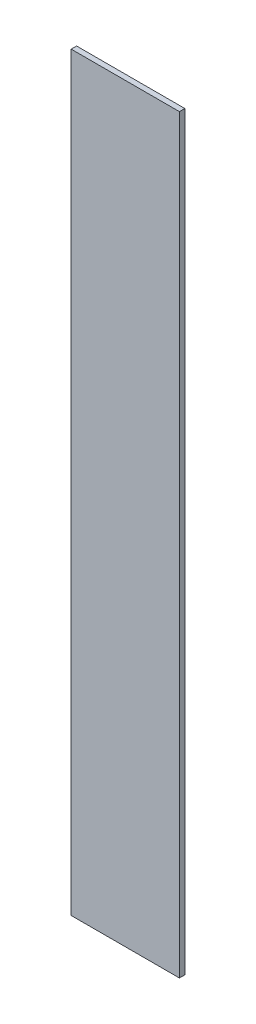
SolidWorks part; units mm, degrees
ref_plane "Plan de face" through (0, 0, 0) normal (0, 0, 1) x (1, 0, 0)
ref_plane "Plan de dessus" through (0, 0, 0) normal (0, 1, 0) x (1, 0, 0)
ref_plane "Plan de droite" through (0, 0, 0) normal (1, 0, 0) x (0, 0, -1)
sketch "Esquisse1" plane through (0, 0, 0) normal (0, 0, 1) x (1, 0, 0)
  line L1 (-60, -416) -> (60, -416)
  line L2 (-60, -416) -> (-60, 416)
  line L3 (-60, 416) -> (60, 416)
  line L4 (60, -416) -> (60, 416)
  line L5 (-60, -416) -> (60, 416) construction
  line L6 (-60, 416) -> (60, -416) construction
  point P0 (0, 0)
  dimension "D1" = 120
  dimension "D2" = 832
extrude "Boss.-Extru.1" add sketch "Esquisse1" along normal blind 6
